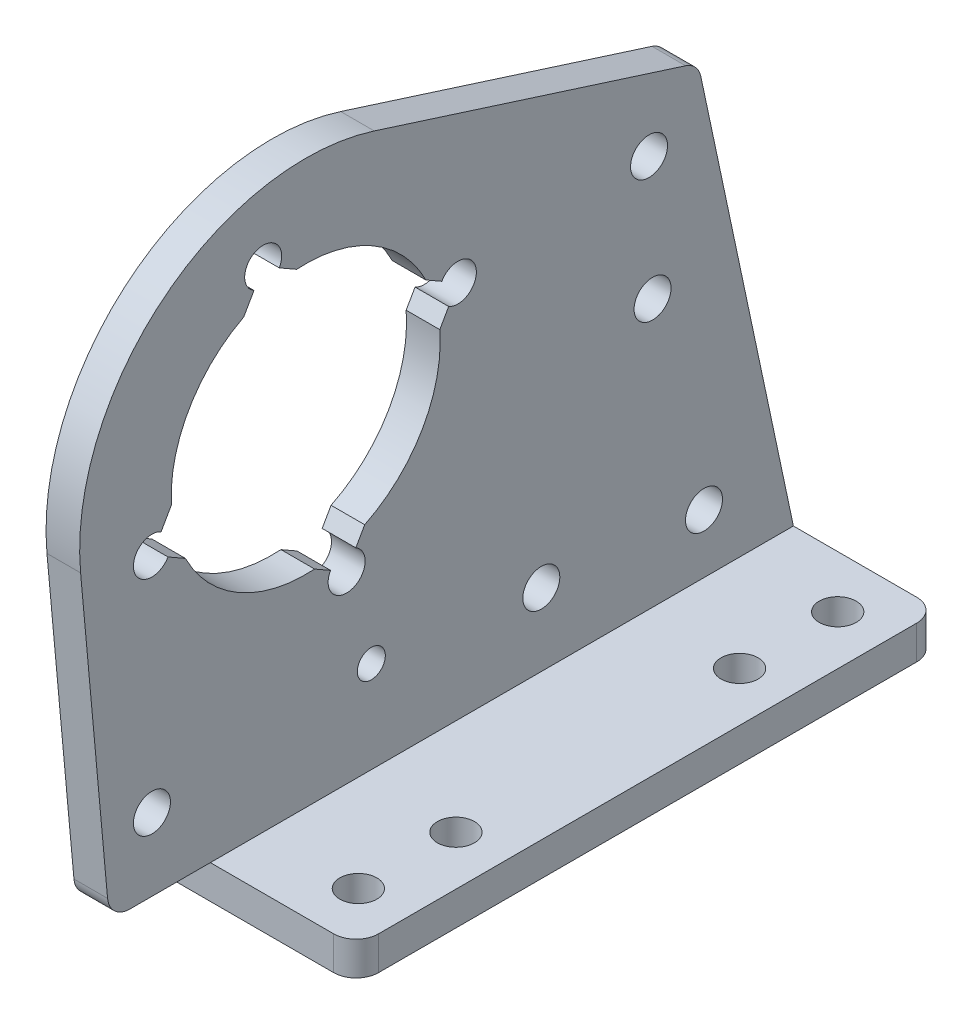
SolidWorks part; units mm, degrees
ref_plane "前视基准面" through (0, 0, 0) normal (0, 0, 1) x (1, 0, 0)
ref_plane "上视基准面" through (0, 0, 0) normal (0, 1, 0) x (1, 0, 0)
ref_plane "右视基准面" through (0, 0, 0) normal (1, 0, 0) x (0, 0, -1)
sketch "草图4" plane through (0, 0, 3) normal (1, 0, 0) x (0, 0, -1)
  line L0 (3, 53) -> (73, 53)
  line L2 (38, 53) -> (38, 13)
  line L3 (3, 0) -> (3, 53)
  line L4 (38, 53) -> (73, 53)
  line L5 (11.75, 48) -> (16.7114, 56.6824)
  line L7 (16.7114, 56.6824) -> (51.4411, 36.8369)
  line L8 (46.4797, 28.1544) -> (51.4411, 36.8369)
  line L9 (55.5, 53) -> (19.7923, 64.3795)
  line L10 (3, 13) -> (64, 13)
  line L11 (11.75, 48) -> (6.7886, 39.3176)
  line L12 (46.4797, 28.1544) -> (41.5183, 19.472)
  line L14 (6.7886, 39.3176) -> (41.5183, 19.472)
  line L15 (3, 13) -> (-0.3134, 49.2816)
  line L16 (34.0763, 46.7597) -> (24.1535, 29.3948)
  line L17 (73, 13) -> (64, 13)
  line L18 (55.5, 53) -> (64, 13)
  circle A0 centre (16.7114, 56.6824) radius 1.65
  circle A1 centre (34.0763, 46.7597) radius 1.65
  circle A2 centre (51.4411, 36.8369) radius 1.65
  circle A3 centre (24.1535, 29.3948) radius 1.65
  circle A4 centre (6.7886, 39.3176) radius 1.65
  circle A5 centre (41.5183, 19.472) radius 1.65
  circle A6 centre (20.4998, 42.9997) radius 12
  circle A7 centre (20.4998, 42.9997) radius 20.1556
  circle A8 centre (51.125, 48) radius 1.65
  circle A9 centre (26.3549, 21.1974) radius 1.25
  circle A10 centre (56.0261, 18.2423) radius 1.65
  circle A11 centre (6.7886, 19.472) radius 1.65
  dimension "D1" = 13
  dimension "D2" = 29.9997
  dimension "D3" = 17.4998
extrude "凸台-拉伸6" add sketch "草图4" along normal blind 3 contours A7 L0 L9 | A7 L7 A2 L8 L12 A5 L14 L2 L10 L18 L0 A10 A8 | A7 L2 L14 A5 L12 L8 A2 L7 | A7 L3 L10 L2 L14 A11 A9 | A7 L15 L3 | L3 A7 | L3 A7 L14 A3 A6 A4 L11 L0 | L0 A7 A6 L5 A0 L7 | L2 A7 L0 A6 L7 A1 | A7 L14 L2 | L14 A7 L2 L7 A1 L16 A6 A3 | L2 A7 L7 | L7 A7 L2
sketch "草图2" plane through (0, 0, 0) normal (1, 0, 0) x (0, 0, -1)
  line L0 (0, 13) -> (9, 13)
  line L2 (0, 13) -> (61, 13) construction
  line L3 (61, 13) -> (9, 13)
  line L4 (61, 13) -> (61, 10)
  line L5 (9, 13) -> (9, 10)
  line L6 (61, 10) -> (9, 10)
extrude "凸台-拉伸5" add sketch "草图2" along normal blind 16
sketch "草图3" plane through (0, 13, 0) normal (0, 1, 0) x (1, 0, 0)
  line L0 (16, 9) -> (0, 9) construction
  line L1 (16, 61) -> (0, 61) construction
  line L2 (3, 0) -> (0, 0) construction
  circle A0 centre (11.6, 13.6) radius 1.65
  circle A1 centre (18.3, 13.6) radius 1.65
  circle A2 centre (11.6, 22.3) radius 1.65
  circle A3 centre (18.3, 22.3) radius 1.65
  circle A4 centre (11.6, 47.6) radius 1.65
  circle A5 centre (18.3, 47.65) radius 1.65
  circle A6 centre (11.6, 56.35) radius 1.65
  circle A7 centre (18.3, 56.35) radius 1.65
  dimension "D1" = 25.3
  dimension "D2" = 4.6
  dimension "D5" = 8.7
  dimension "D6" = 8.7
  dimension "D3" = 4.65
  dimension "D4" = 9
extrude "切除-拉伸1" cut sketch "草图3" against normal blind 22 and the other way through all contours A0 | A2 | A6 | A4
fillet "圆角1" radius 2 4 edges at (16, 11.5, -61) (1.5, 13, 0) (16, 11.5, -9)
